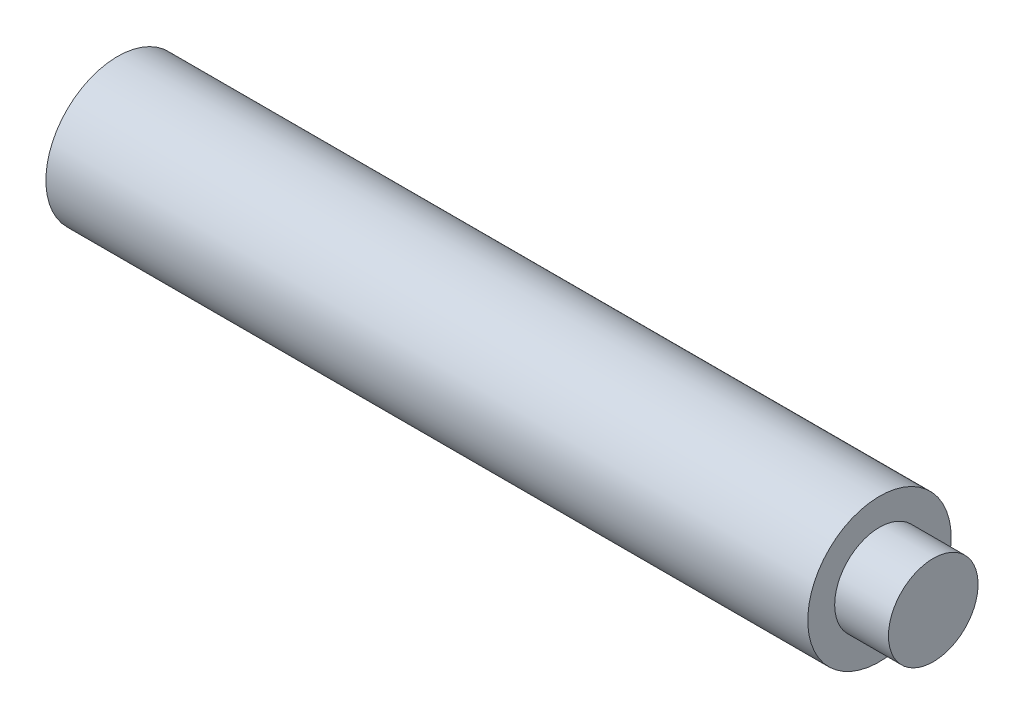
SolidWorks part; units mm, degrees
ref_plane "Front Plane" through (0, 0, 0) normal (0, 0, 1) x (1, 0, 0)
ref_plane "Top Plane" through (0, 0, 0) normal (0, 1, 0) x (1, 0, 0)
ref_plane "Right Plane" through (0, 0, 0) normal (1, 0, 0) x (0, 0, -1)
sketch "Sketch1" plane through (0, 0, 0) normal (1, 0, 0) x (0, 0, -1)
  circle A0 centre (0, 0) radius 101.6
  dimension "D1" = 203.2
extrude "Boss-Extrude1" add sketch "Sketch1" along normal mid plane 1079.5
sketch "Sketch2" plane through (539.75, 0, 0) normal (1, 0, 0) x (0, 0, -1)
  circle A0 centre (0, 0) radius 63.5
  dimension "D1" = 127
extrude "Boss-Extrude2" add sketch "Sketch2" along normal blind 76.2
